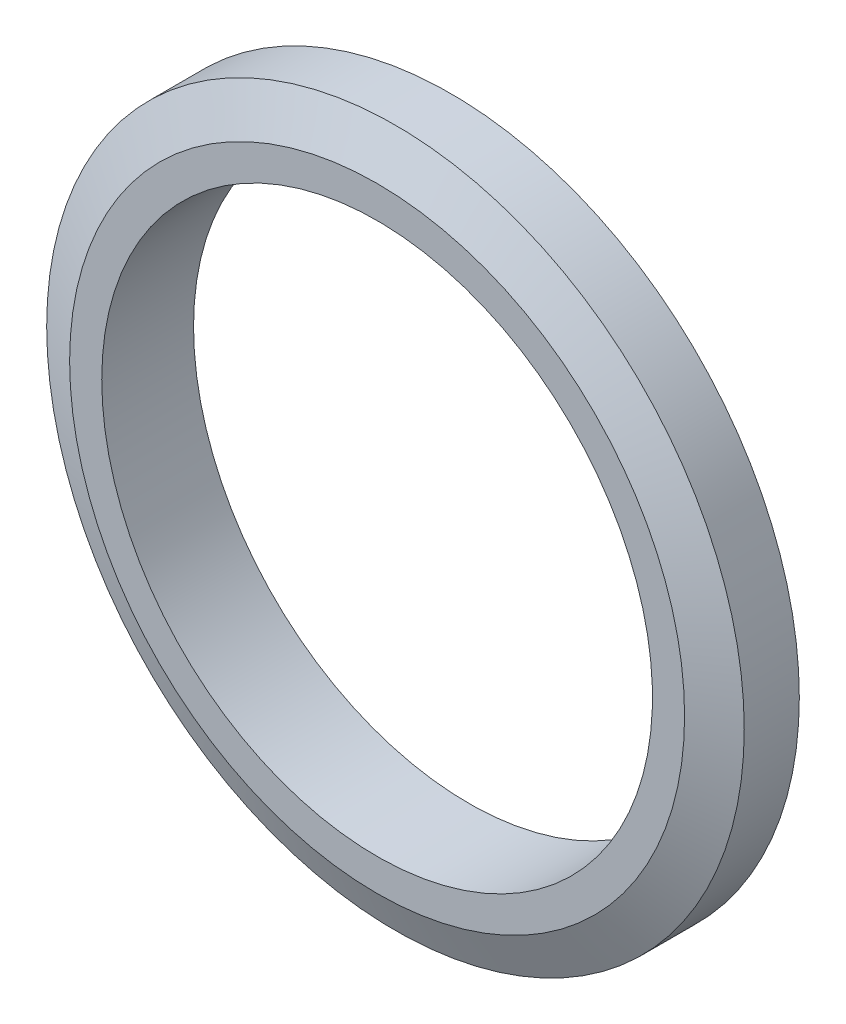
SolidWorks part; units mm, degrees
material "Plain Carbon Steel"
ref_plane "Front Plane" through (0, 0, 0) normal (0, 0, 1) x (1, 0, 0)
ref_plane "Top Plane" through (0, 0, 0) normal (0, 1, 0) x (1, 0, 0)
ref_plane "Right Plane" through (0, 0, 0) normal (1, 0, 0) x (0, 0, -1)
ref_plane "Plane1" through (0, 295, 0) normal (0, -1, 0) x (1, 0, 0)
sketch "Sketch1" plane through (0, 295, 0) normal (0, -1, 0) x (1, 0, 0)
  line L0 (67.6, 15.4) -> (67.6, 16.6)
  line L1 (67.6, 16.6) -> (66.7, 17)
  line L2 (66.7, 17) -> (66, 17)
  line L3 (66, 17) -> (66, 15)
  line L4 (66, 15) -> (66.7, 15)
  line L5 (66.7, 15) -> (67.6, 15.4)
  line L6 (60, 17) -> (60, 15) construction
revolve "Revolve1" add sketch "Sketch1" angle 360 about L6
